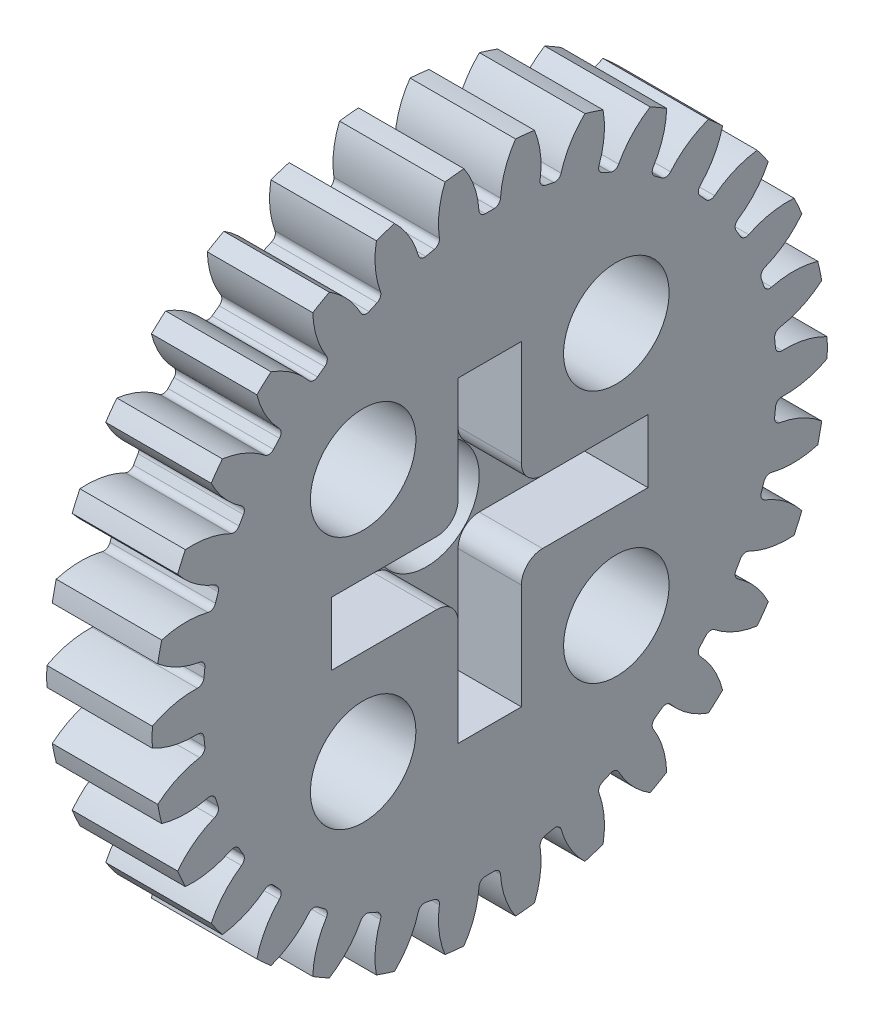
SolidWorks part; units mm, degrees
ref_plane "Front Plane" through (0, 0, 0) normal (0, 0, 1) x (1, 0, 0)
ref_plane "Top Plane" through (0, 0, 0) normal (0, 1, 0) x (1, 0, 0)
ref_plane "Right Plane" through (0, 0, 0) normal (1, 0, 0) x (0, 0, -1)
sketch "Sketch1" plane through (0, 0, 0) normal (1, 0, 0) x (0, 0, -1)
  circle A0 centre (0, 0) radius 16
  dimension "D1" = 32
extrude "Boss-Extrude1" add sketch "Sketch1" along normal blind 5
sketch "Sketch2" plane through (5, 0, 0) normal (1, 0, 0) x (0, 0, -1)
  line L0 (0, 0) -> (0, 19.2279) construction
  line L1 (-0.21, 13.6) -> (0.21, 13.6)
  arc A0 (0.5094, 13.88) -> (2.08, 16.88) centre (4.6946, 13.6) cw
  arc A1 (0.21, 13.6) -> (0.5094, 13.88) centre (0.21, 13.9) ccw
  arc A2 (-0.21, 13.6) -> (-0.5094, 13.88) centre (-0.21, 13.9) cw
  arc A3 (-0.5094, 13.88) -> (-2.08, 16.88) centre (-4.6946, 13.6) ccw
  arc A4 (-2.08, 16.88) -> (2.08, 16.88) centre (0, -0.9994) cw
  point P1 (-0.5, 13.6)
  point P2 (-2.08, 16.8957)
  point P7 (2.08, 16.9958)
  point P8 (0, 0)
  point P12 (0.5, 13.6)
  point P18 (0, 13.6)
  dimension "D5" = 0.3
  dimension "D6" = 18
  dimension "D1" = 0.5
  dimension "D2" = 13.6
  dimension "D3" = 1.58
  dimension "D4" = 3.28
extrude "Cut-Extrude1" cut sketch "Sketch2" against normal through all
pattern_circular "CirPattern1" count 30 over 360 about axis through (0, 0, 0) along (1, 0, 0) of "Cut-Extrude1"
sketch "Sketch4" plane through (5, 0, 0) normal (1, 0, 0) x (0, 0, -1)
  line L0 (7.5, 0) -> (-7.5, 0) construction
  line L1 (-1.5, 7.5) -> (1.5, 7.5)
  line L2 (-1.5, 7.5) -> (-1.5, 1.5)
  line L3 (-1.5, -7.5) -> (1.5, -7.5)
  line L4 (1.5, 7.5) -> (1.5, 1.5)
  line L5 (-7.5, 1.5) -> (-1.5, 1.5)
  line L6 (-7.5, 1.5) -> (-7.5, -1.5)
  line L7 (-7.5, -1.5) -> (-1.5, -1.5)
  line L8 (7.5, 1.5) -> (7.5, -1.5)
  line L9 (0, 7.5) -> (0, -7.5) construction
  line L10 (1.5, 1.5) -> (7.5, 1.5)
  line L11 (-1.5, -1.5) -> (-1.5, -7.5)
  line L12 (1.5, -1.5) -> (7.5, -1.5)
  line L13 (1.5, -1.5) -> (1.5, -7.5)
  point P10 (7.5, -3.1966)
  point P11 (0, 0)
  dimension "D1" = 3
  dimension "D2" = 3
  dimension "D3" = 15
  dimension "D4" = 15
extrude "Cut-Extrude2" cut sketch "Sketch4" against normal blind 3
fillet "Fillet1" radius 1 4 edges at (3.5, -1.5, 1.5) (3.5, -1.5, -1.5) (3.5, 1.5, -1.5) (3.5, 1.5, 1.5)
sketch "Sketch5" plane through (5, 0, 0) normal (1, 0, 0) x (0, 0, -1)
  line L0 (0, 0) -> (0, 16) construction
  line L1 (0, 0) -> (16, 0) construction
  circle A0 centre (6, 6) radius 2.5
  circle A1 centre (0, 0) radius 16 construction
  circle A2 centre (6, -6) radius 2.5
  circle A3 centre (-6, 6) radius 2.5
  circle A4 centre (-6, -6) radius 2.5
  circle A5 centre (0, 0) radius 2.5
  dimension "D3" = 5
  dimension "D4" = 5
  dimension "D1" = 6
  dimension "D2" = 6
extrude "Cut-Extrude3" cut sketch "Sketch5" against normal through all
